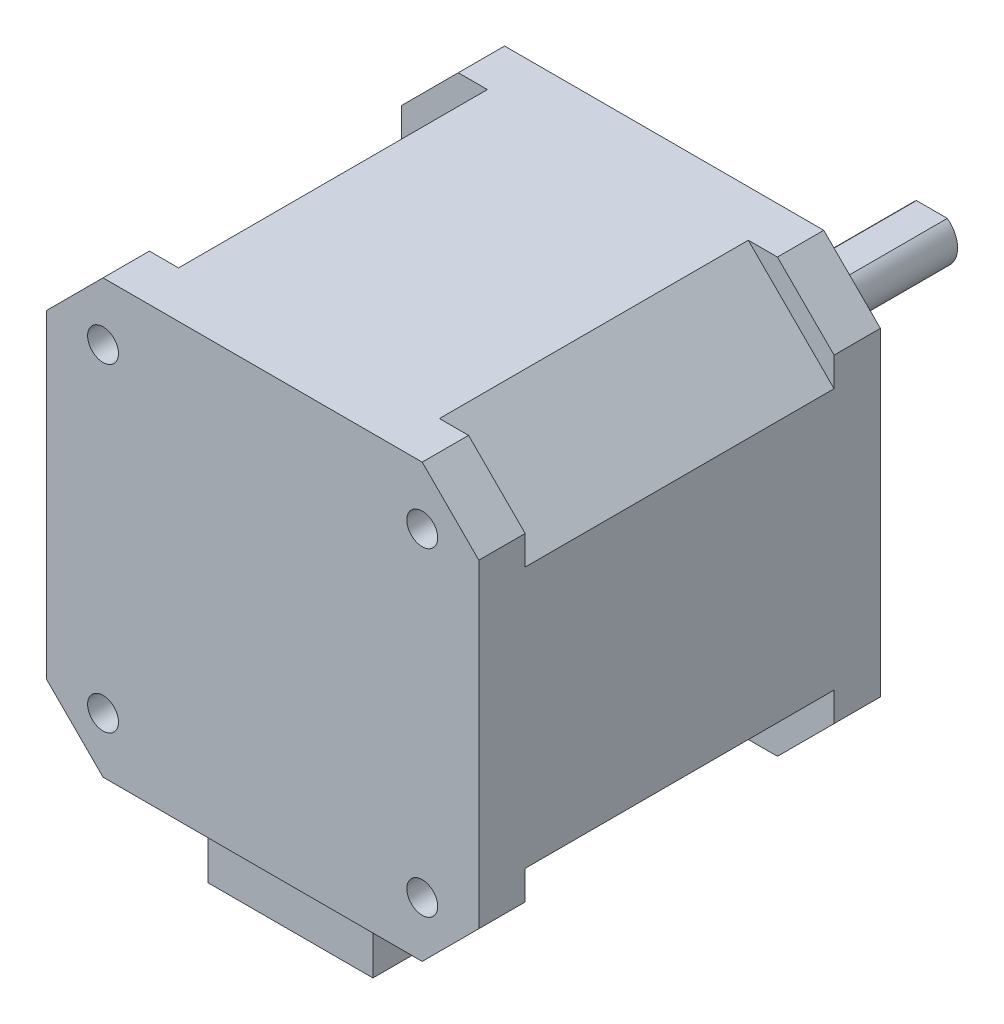
SolidWorks part; units mm, degrees
ref_plane "Front Plane" through (0, 0, 0) normal (0, 0, 1) x (1, 0, 0)
ref_plane "Top Plane" through (0, 0, 0) normal (0, 1, 0) x (1, 0, 0)
ref_plane "Right Plane" through (0, 0, 0) normal (1, 0, 0) x (0, 0, -1)
sketch "Sketch1" plane through (0, 0, 0) normal (0, 0, 1) x (1, 0, 0)
  line L0 (0, 36.5) -> (5.5, 42)
  line L1 (5.5, 0) -> (36.5, 0)
  line L2 (0, 5.5) -> (0, 36.5)
  line L3 (5.5, 42) -> (36.5, 42)
  line L4 (42, 5.5) -> (42, 36.5)
  line L5 (46.9904, 21) -> (-17.2499, 21) construction
  line L6 (21, 53.7645) -> (21, 0) construction
  line L7 (0, 5.5) -> (5.5, 0)
  line L8 (42, 5.5) -> (36.5, 0)
  line L9 (42, 36.5) -> (36.5, 42)
  circle A0 centre (5.5, 36.3827) radius 1.5
  circle A1 centre (36.5, 36.3827) radius 1.5
  circle A2 centre (36.5, 5.3827) radius 1.5
  circle A3 centre (5.5, 5.3827) radius 1.5
  point P2 (0, 42)
  point P7 (21, 42)
  dimension "D2" = 15.5
  dimension "D3" = 2
  dimension "3" = 3
  dimension "D4" = 2
extrude "Boss-Extrude1" add sketch "Sketch1" along normal blind 4.5
sketch "Sketch2" plane through (0, 0, 4.5) normal (0, 0, 1) x (1, 0, 0)
  line L0 (8.3284, 42) -> (0, 33.6716)
  line L1 (0, 8.3284) -> (8.3284, 0)
  line L2 (33.6716, 0) -> (42, 8.3284)
  line L3 (42, 33.6716) -> (33.6716, 42)
  line L4 (1.4142, 6.9142) -> (6.9142, 1.4142) construction
  line L5 (6.9142, 40.5858) -> (1.4142, 35.0858) construction
  line L6 (40.5858, 35.0858) -> (35.0858, 40.5858) construction
  line L7 (35.0858, 1.4142) -> (40.5858, 6.9142) construction
  line L8 (36.5, 42) -> (5.5, 42)
  line L9 (5.5, 42) -> (0, 36.5)
  line L10 (0, 36.5) -> (0, 5.5)
  line L11 (0, 5.5) -> (5.5, 0)
  line L12 (5.5, 0) -> (36.5, 0)
  line L13 (36.5, 0) -> (42, 5.5)
  line L14 (42, 5.5) -> (42, 36.5)
  line L15 (42, 36.5) -> (36.5, 42)
  line L16 (33.6716, 42) -> (8.3284, 42)
  line L17 (5.5, 42) -> (0, 36.5) construction
  line L18 (0, 33.6716) -> (0, 8.3284)
  line L19 (0, 5.5) -> (5.5, 0) construction
  line L20 (8.3284, 0) -> (33.6716, 0)
  line L21 (36.5, 0) -> (42, 5.5) construction
  line L22 (42, 8.3284) -> (42, 33.6716)
  line L23 (42, 36.5) -> (36.5, 42) construction
  dimension "D2" = 2
  dimension "D1" = 0
extrude "Boss-Extrude2" add sketch "Sketch2" along normal blind 30
sketch "Sketch3" plane through (0, 0, 34.5) normal (0, 0, 1) x (1, 0, 0)
  line L8 (36.5, 42) -> (5.5, 42)
  line L9 (42, 36.5) -> (36.5, 42)
  line L10 (42, 5.5) -> (42, 36.5)
  line L11 (36.5, 0) -> (42, 5.5)
  line L12 (5.5, 0) -> (36.5, 0)
  line L13 (0, 5.5) -> (5.5, 0)
  line L14 (0, 36.5) -> (0, 5.5)
  line L15 (5.5, 42) -> (0, 36.5)
  line L16 (36.5, 42) -> (5.5, 42)
  line L17 (42, 36.5) -> (36.5, 42)
  line L18 (42, 5.5) -> (42, 36.5)
  line L19 (36.5, 0) -> (42, 5.5)
  line L20 (5.5, 0) -> (36.5, 0)
  line L21 (0, 5.5) -> (5.5, 0)
  line L22 (0, 36.5) -> (0, 5.5)
  line L23 (5.5, 42) -> (0, 36.5)
  circle A0 centre (5.5, 5.3827) radius 1.5 construction
  circle A1 centre (36.5, 5.3827) radius 1.5 construction
  circle A2 centre (5.5, 36.3827) radius 1.5 construction
  circle A3 centre (36.5, 36.3827) radius 1.5 construction
  circle A4 centre (5.5, 5.3827) radius 1.5
  circle A5 centre (36.5, 5.3827) radius 1.5
  circle A6 centre (5.5, 36.3827) radius 1.5
  circle A7 centre (36.5, 36.3827) radius 1.5
  dimension "D1" = 0
extrude "Boss-Extrude3" add sketch "Sketch3" along normal blind 4.5
sketch "Sketch5" plane through (0, 0, 0) normal (0, 0, -1) x (-1, 0, 0)
  line L0 (-21, 42) -> (-21, 0) construction
  line L1 (-42, 21) -> (0, 21) construction
  line L8 (-5.5, 42) -> (-36.5, 42)
  line L9 (-36.5, 42) -> (-42, 36.5)
  line L10 (-42, 36.5) -> (-42, 5.5)
  line L11 (-42, 5.5) -> (-36.5, 0)
  line L12 (-36.5, 0) -> (-5.5, 0)
  line L13 (-5.5, 0) -> (0, 5.5)
  line L14 (0, 5.5) -> (0, 36.5)
  line L15 (0, 36.5) -> (-5.5, 42)
  line L16 (-5.5, 42) -> (-36.5, 42) construction
  line L17 (-36.5, 42) -> (-42, 36.5) construction
  line L18 (-42, 36.5) -> (-42, 5.5) construction
  line L19 (-42, 5.5) -> (-36.5, 0) construction
  line L20 (-36.5, 0) -> (-5.5, 0) construction
  line L21 (-5.5, 0) -> (0, 5.5) construction
  line L22 (0, 5.5) -> (0, 36.5) construction
  line L23 (0, 36.5) -> (-5.5, 42) construction
  circle A0 centre (-21, 21) radius 11
  dimension "D4" = 22
  dimension "D2" = 42
  dimension "D3" = 42
  dimension "D1" = 0
extrude "Boss-Extrude4" add sketch "Sketch5" along normal blind 2
sketch "Sketch6" plane through (0, 0, -2) normal (0, 0, -1) x (-1, 0, 0)
  circle A0 centre (-21, 21) radius 2.5
  circle A1 centre (-21, 21) radius 11
  circle A2 centre (-21, 21) radius 11 construction
  dimension "D1" = 0
extrude "Boss-Extrude5" add sketch "Sketch6" along normal blind 24
sketch "Sketch7" plane through (0, 0, 0) normal (-1, 0, 0) x (0, 0, 1)
  line L0 (-26, 23.5) -> (-26, 18.5) construction
  line L1 (-26, 23.5) -> (-26, 18.5) construction
  line L2 (-2, 23.5) -> (-2, 18.5) construction
  line L3 (-2, 23.5) -> (-2, 18.5) construction
  line L4 (-26, 23.5) -> (-12, 23.5)
  line L5 (-2, 23.5) -> (-26, 23.5) construction
  line L6 (-12, 23.5) -> (-12, 23)
  line L7 (-12, 23) -> (-26, 23)
  line L8 (-26, 23) -> (-26, 23.5)
  line L10 (-26, 18.5) -> (-2, 18.5) construction
  dimension "D1" = 14
  dimension "D2" = 4.5
  dimension "D3" = 14
extrude "Cut-Extrude2" cut sketch "Sketch7" against normal through all
sketch "Sketch8" plane through (0, 0, 0) normal (0, -1, 0) x (1, 0, 0)
  line L0 (21, 36.2858) -> (21, 0) construction
  line L3 (5.5, 39) -> (36.5, 39) construction
  line L4 (5.5, 0) -> (36.5, 0) construction
  line L5 (13, 36.2858) -> (21, 36.2858)
  line L6 (21, 39) -> (13, 39)
  line L8 (21, 28) -> (13, 28)
  line L9 (13, 36.2858) -> (13, 28)
  line L10 (21, 28) -> (29, 28)
  line L11 (21, 36.2858) -> (29, 36.2858)
  line L12 (29, 36.2858) -> (29, 28)
  dimension "D1" = 39
  dimension "D2" = 11
  dimension "D3" = 8
  dimension "D4" = 8
  dimension "D5" = 8
  dimension "D6" = 8
  dimension "D7" = 8.2858
extrude "Boss-Extrude6" add sketch "Sketch8" along normal blind 6.5 contours L0 L5 L9 L8 | L11 L0 L10 L12
